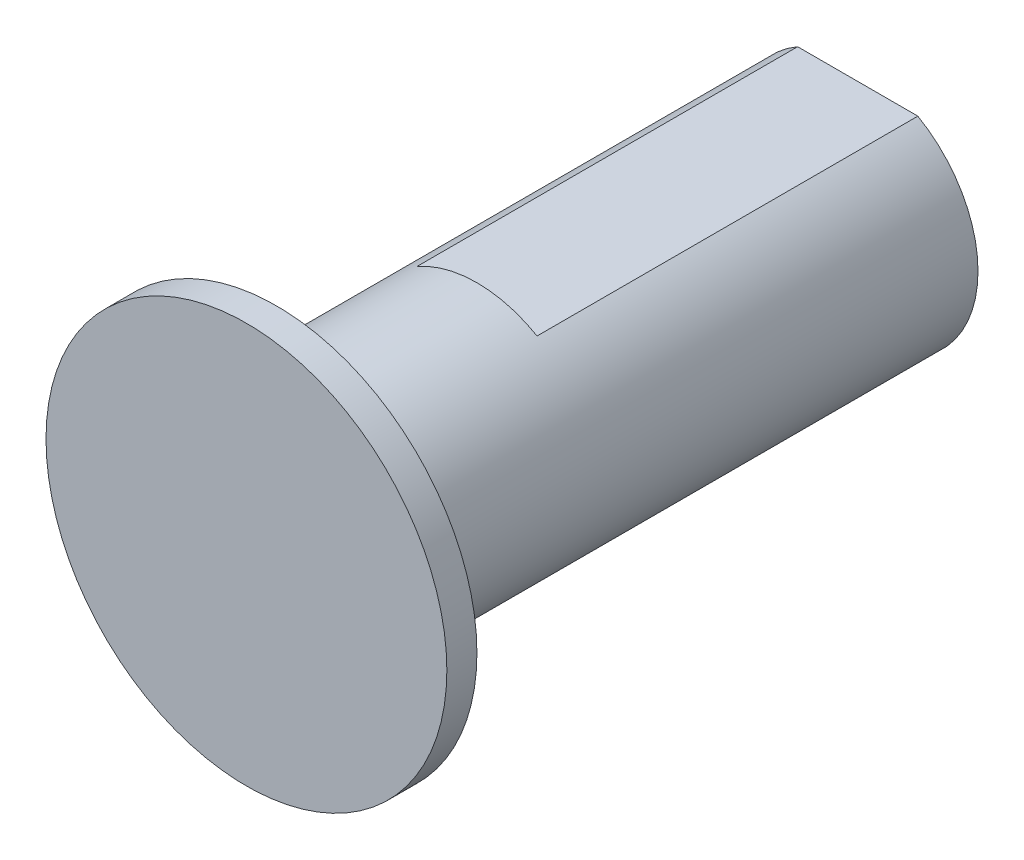
SolidWorks part; units mm, degrees
ref_plane "Front Plane" through (0, 0, 0) normal (0, 0, 1) x (1, 0, 0)
ref_plane "Top Plane" through (0, 0, 0) normal (0, 1, 0) x (1, 0, 0)
ref_plane "Right Plane" through (0, 0, 0) normal (1, 0, 0) x (0, 0, -1)
sketch "Sketch1" plane through (0, 0, 0) normal (0, 0, 1) x (1, 0, 0)
  line L0 (-3, 5.1962) -> (3, 5.1962)
  circle A0 centre (0, 0) radius 6
  dimension "D1" = 12
  dimension "D2" = 6
extrude "Boss-Extrude1" add sketch "Sketch1" along normal blind 29 contours A0
sketch "Sketch2" plane through (0, 0, 0) normal (0, 0, -1) x (-1, 0, 0)
  line L0 (-3, 5.1962) -> (3, 5.1962)
  circle A1 centre (0, 0) radius 6 construction
  circle A2 centre (0, 0) radius 6
  circle M3 centre (0, 0) radius 6
  dimension "D1" = 6
extrude "Cut-Extrude1" cut sketch "Sketch2" against normal blind 19 contours L0 M3
sketch "Sketch3" plane through (0, 0, 29) normal (0, 0, 1) x (1, 0, 0)
  circle A0 centre (0, 0) radius 10
  dimension "D1" = 20
extrude "Boss-Extrude2" add sketch "Sketch3" along normal blind 1.5
